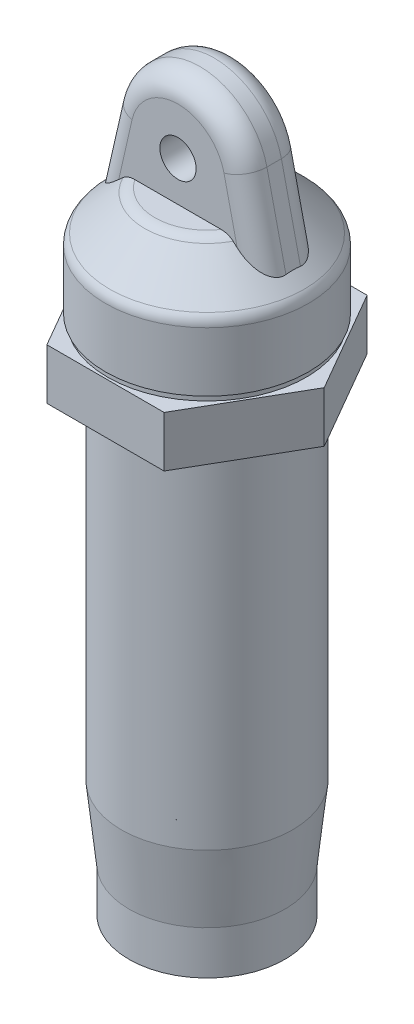
SolidWorks part; units mm, degrees
ref_plane "Front Plane" through (0, 0, 0) normal (0, 0, 1) x (1, 0, 0)
ref_plane "Top Plane" through (0, 0, 0) normal (0, 1, 0) x (1, 0, 0)
ref_plane "Right Plane" through (0, 0, 0) normal (1, 0, 0) x (0, 0, -1)
sketch "Sketch1" plane through (0, 0, 0) normal (0, 1, 0) x (1, 0, 0)
  circle A0 centre (0, 0) radius 5.375
  dimension "D1" = 10.75
extrude "Boss-Extrude1" add sketch "Sketch1" along normal blind 3
sketch "Sketch2" plane through (0, 3, 0) normal (0, 1, 0) x (1, 0, 0)
  circle A0 centre (0, 0) radius 5.375
  circle A1 centre (0, 0) radius 5.375 construction
extrude "Boss-Extrude2" add sketch "Sketch2" along normal blind 5 draft 6 draft outward yes
sketch "Sketch3" plane through (0, 8, 0) normal (0, 1, 0) x (1, 0, 0)
  circle A0 centre (0, 0) radius 5.9005
  circle A1 centre (0, 0) radius 5.9005 construction
extrude "Boss-Extrude3" add sketch "Sketch3" along normal blind 24
sketch "Sketch5" plane through (0, 32, 0) normal (0, 1, 0) x (1, 0, 0)
  line L1 (-4.0415, 7) -> (-8.0829, 0)
  line L2 (-8.0829, 0) -> (-4.0415, -7)
  line L3 (-4.0415, -7) -> (4.0415, -7)
  line L4 (4.0415, -7) -> (8.0829, 0)
  line L5 (8.0829, 0) -> (4.0415, 7)
  line L6 (4.0415, 7) -> (-4.0415, 7)
  circle A0 centre (0, 0) radius 7 construction
  dimension "D1" = 14
extrude "Boss-Extrude4" add sketch "Sketch5" along normal blind 3.5
sketch "Sketch6" plane through (0, 35.5, 0) normal (0, 1, 0) x (1, 0, 0)
  circle A0 centre (0, 0) radius 6.8468
extrude "Boss-Extrude5" add sketch "Sketch6" along normal blind 0.3969
sketch "Sketch7" plane through (0, 35.8969, 0) normal (0, 1, 0) x (1, 0, 0)
  circle A0 centre (0, 0) radius 7
  dimension "D1" = 14
extrude "Boss-Extrude6" add sketch "Sketch7" along normal blind 4.5
sketch "Sketch8" plane through (0, 40.3969, 0) normal (0, 1, 0) x (1, 0, 0)
  circle A0 centre (0, 0) radius 7
  circle A1 centre (0, 0) radius 7 construction
extrude "Boss-Extrude7" add sketch "Sketch8" along normal blind 3 draft 45
sketch "Sketch9" plane through (0, 0, 0) normal (0, 0, 1) x (1, 0, 0)
  line L0 (4.6316, 47.2007) -> (6.1281, 40.6234)
  line L1 (-4.6316, 47.2007) -> (-6.1281, 40.6234)
  line L2 (-6.1281, 40.6234) -> (6.1281, 40.6234)
  line L3 (0, 40.6234) -> (0, 40.8388) construction
  line L4 (0, 50.8969) -> (4.9173, 50.8969) construction
  line L5 (-6.8468, 35.8969) -> (6.8468, 35.8969) construction
  line L6 (0, 47.3969) -> (2.8337, 47.3969) construction
  circle A0 centre (0, 46.1469) radius 1.25
  circle A1 centre (0, 46.1469) radius 4.75
  point P14 (0, 0)
  point P17 (-5.7378, 40.5999)
  point P18 (0, 0)
  point P19 (6.1281, 40.6234)
  dimension "D2" = 2.5
  dimension "D1" = 15
  dimension "D3" = 3.5
extrude "Boss-Extrude8" add sketch "Sketch9" along normal blind 2 and the other way blind 2 contours A1 A0 | A1 L1 L2 L0
fillet "Fillet1" radius 1 3 edges at (0, 43.3969, 4) (0, 40.3969, 7) (0, 43.3969, -4)
fillet "Fillet2" radius 1.5 6 edges at (-5.3324, 44.1208, -2) (0, 50.8969, -2) (-5.3324, 44.1208, 2) (0, 50.8969, 2) (5.3324, 44.1208, -2) (5.3324, 44.1208, 2)
sketch "Sketch10" plane through (0, 0, 0) normal (0, -1, 0) x (1, 0, 0)
  circle A0 centre (0, 0) radius 1.5
  dimension "D1" = 3
extrude "Cut-Extrude1" cut sketch "Sketch10" against normal up to surface (35.5 mm away) up to face at (0, 35.5, 6.8468)
